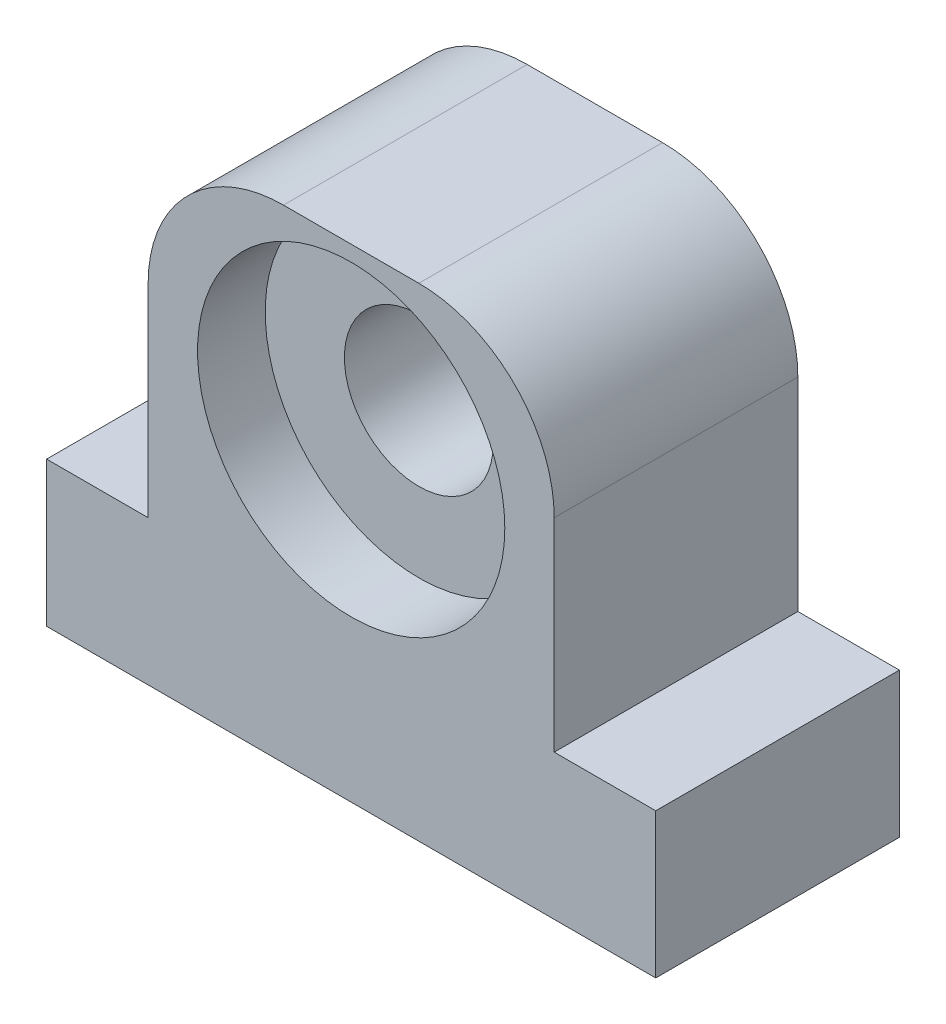
SolidWorks part; units mm, degrees
ref_plane "Front Plane" through (0, 0, 0) normal (0, 0, 1) x (1, 0, 0)
ref_plane "Top Plane" through (0, 0, 0) normal (0, 1, 0) x (1, 0, 0)
ref_plane "Right Plane" through (0, 0, 0) normal (1, 0, 0) x (0, 0, -1)
sketch "Sketch1" plane through (0, 0, 0) normal (0, 1, 0) x (1, 0, 0)
  line L1 (-22.5, 9) -> (22.5, 9)
  line L2 (-22.5, 9) -> (-22.5, -9)
  line L3 (-22.5, -9) -> (22.5, -9)
  line L4 (22.5, 9) -> (22.5, -9)
  line L5 (-22.5, 9) -> (22.5, -9) construction
  line L6 (-22.5, -9) -> (22.5, 9) construction
  point P0 (0, 0)
  dimension "D1" = 45
  dimension "D2" = 18
extrude "Boss-Extrude1" add sketch "Sketch1" along normal blind 3
sketch "Sketch2" plane through (0, 3, 0) normal (0, 1, 0) x (1, 0, 0)
  line L0 (-22.5, -9) -> (22.5, -9) construction
  line L1 (-15, 9) -> (15, 9)
  line L2 (-15, 9) -> (-15, -9)
  line L3 (-15, -9) -> (15, -9)
  line L4 (15, 9) -> (15, -9)
  line L5 (-15, 9) -> (15, -9) construction
  line L6 (-15, -9) -> (15, 9) construction
  point P0 (0, 0)
  dimension "D1" = 30
extrude "Boss-Extrude3" add sketch "Sketch2" along normal blind 25
sketch "Sketch5" plane through (0, 0, 9) normal (0, 0, 1) x (1, 0, 0)
  line L0 (0, 28) -> (0, 0) construction
  line L1 (-15, 28) -> (15, 28) construction
  line L2 (-15, 15.5) -> (15, 15.5) construction
  line L3 (-15, 28) -> (-15, 3) construction
  line L4 (15, 28) -> (15, 3) construction
  circle A0 centre (0, 15.5) radius 5.5
  dimension "D1" = 11
extrude "Cut-Extrude3" cut sketch "Sketch5" against normal blind 25
sketch "Sketch6" plane through (0, 0, 9) normal (0, 0, 1) x (1, 0, 0)
  circle A0 centre (0, 15.5) radius 11.35
  dimension "D1" = 22.7
extrude "Cut-Extrude4" cut sketch "Sketch6" against normal blind 5
fillet "Fillet2" radius 10 2 edges at (-15, 28, 0) (15, 28, 0)
sketch "Sketch7" plane through (0, 0, 0) normal (0, -1, 0) x (1, 0, 0)
  line L1 (-22.5, 9) -> (22.5, 9)
  line L2 (-22.5, 9) -> (-22.5, -9)
  line L3 (-22.5, -9) -> (22.5, -9)
  line L4 (22.5, 9) -> (22.5, -9)
extrude "Boss-Extrude4" add sketch "Sketch7" along normal blind 4
sketch "Sketch8" plane through (0, -4, 0) normal (0, -1, 0) x (1, 0, 0)
  line L1 (-22.5, 9) -> (22.5, 9)
  line L2 (-22.5, 9) -> (-22.5, -9)
  line L3 (-22.5, -9) -> (22.5, -9)
  line L4 (22.5, 9) -> (22.5, -9)
extrude "Boss-Extrude5" add sketch "Sketch8" along normal blind 3.7
